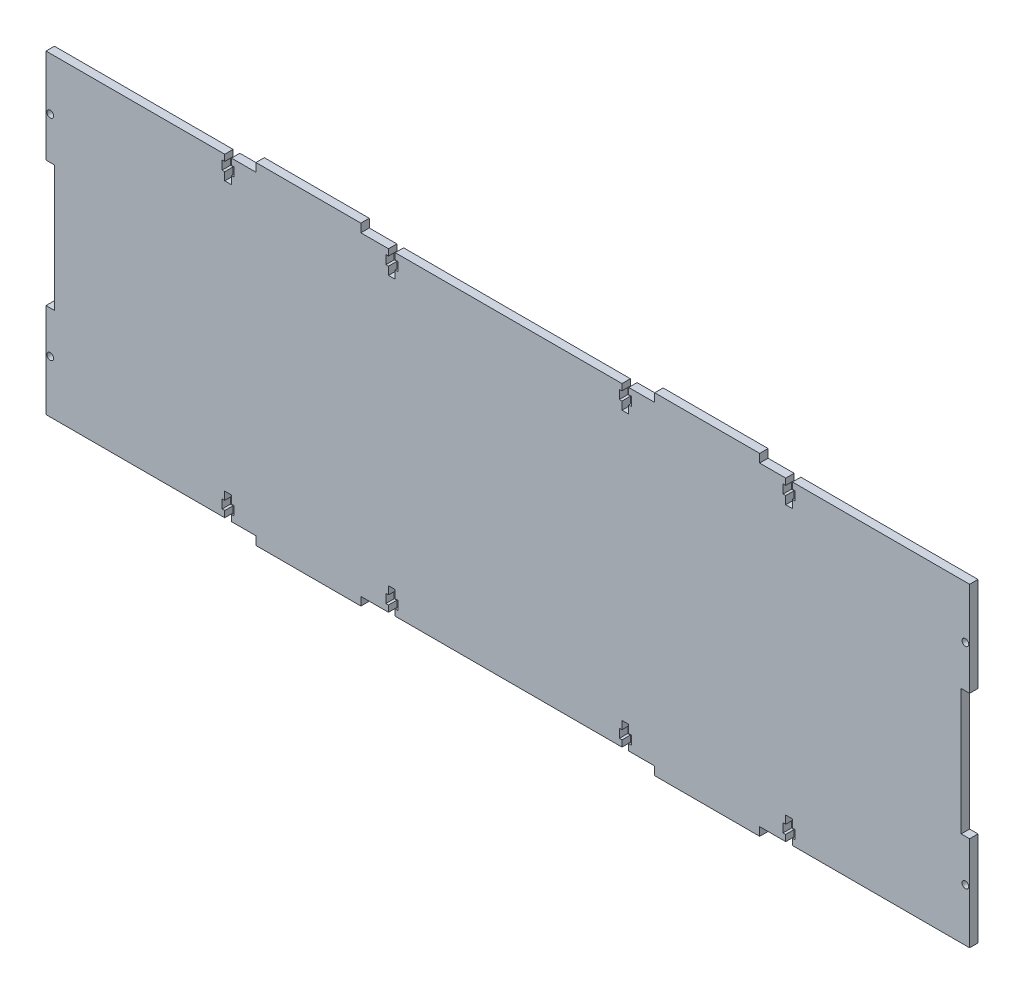
SolidWorks part; units mm, degrees
ref_plane "Plan de face" through (0, 0, 0) normal (0, 0, 1) x (1, 0, 0)
ref_plane "Plan de dessus" through (0, 0, 0) normal (0, 1, 0) x (1, 0, 0)
ref_plane "Plan de droite" through (0, 0, 0) normal (1, 0, 0) x (0, 0, -1)
sketch "Esquisse1" plane through (0, 0, 0) normal (0, 0, 1) x (1, 0, 0)
  line L1 (220, -75) -> (-220, -75)
  line L2 (220, -75) -> (220, 75)
  line L3 (220, 75) -> (-220, 75)
  line L4 (-220, -75) -> (-220, 75)
  line L5 (220, -75) -> (-220, 75) construction
  line L6 (220, 75) -> (-220, -75) construction
  point P0 (0, 0)
  dimension "D1" = 440
  dimension "D2" = 150
extrude "Boss.-Extru.1" add sketch "Esquisse1" along normal blind 4
sketch "Esquisse2" plane through (0, 0, 4) normal (0, 0, 1) x (1, 0, 0)
  line L0 (-220, 75) -> (-220, -75) construction
  line L1 (-216, 30) -> (-220, 30)
  line L2 (-216, 30) -> (-216, -30)
  line L3 (-216, -30) -> (-220, -30)
  line L4 (-220, 30) -> (-220, -30)
  line L5 (-216, -30) -> (-220, -30) construction
  line L6 (220, 30) -> (216, 30) construction
  line L7 (216, 30) -> (220, 30)
  line L8 (216, 30) -> (216, -30)
  line L9 (216, -30) -> (220, -30)
  line L10 (220, 30) -> (220, -30)
  line L11 (220, -30) -> (216, -30) construction
  line L12 (220, -75) -> (220, 75) construction
  line L13 (216, -30) -> (216, 30) construction
  dimension "D1" = 0
extrude "Enlèv. mat.-Extru.1" cut sketch "Esquisse2" against normal blind 4
sketch "Esquisse3" plane through (0, 0, 4) normal (0, 0, 1) x (1, 0, 0)
  line L0 (-70, -75) -> (-70, -79) construction
  line L1 (-120, -79) -> (-70, -79)
  line L2 (-120, -79) -> (-120, -75)
  line L3 (-120, -75) -> (-70, -75)
  line L4 (-70, -79) -> (-70, -75)
  line L5 (-220, -75) -> (220, -75) construction
  line L6 (120, -75) -> (120, -79) construction
  line L7 (70, -79) -> (120, -79)
  line L8 (70, -79) -> (70, -75)
  line L9 (70, -75) -> (120, -75)
  line L10 (120, -79) -> (120, -75)
  line L11 (-90.2276, 0) -> (85.2541, 0) construction
  line L12 (70, 79) -> (70, 75)
  line L13 (70, 79) -> (120, 79)
  line L14 (70, 75) -> (120, 75)
  line L15 (120, 79) -> (120, 75)
  line L16 (-70, 79) -> (-70, 75)
  line L17 (-120, 79) -> (-70, 79)
  line L18 (-120, 75) -> (-70, 75)
  line L19 (-120, 79) -> (-120, 75)
extrude "Boss.-Extru.2" add sketch "Esquisse3" against normal blind 4
sketch "Esquisse4" plane through (0, 0, 4) normal (0, 0, 1) x (1, 0, 0)
  line L0 (220, 75) -> (120, 75) construction
  line L1 (132.4, 75) -> (135.6, 75)
  line L2 (132.4, 75) -> (132.4, 72)
  line L3 (132.4, 64) -> (135.6, 64)
  line L5 (132.4, 79) -> (132.4, 75) construction
  line L6 (220.3751, 79) -> (120, 79) construction
  line L7 (132.4, 67.8) -> (131.15, 67.8)
  line L8 (136.85, 67.8) -> (135.6, 67.8)
  line L9 (136.85, 67.8) -> (136.85, 72)
  line L10 (136.85, 72) -> (135.6, 72)
  line L11 (131.15, 67.8) -> (131.15, 72)
  line L12 (136.85, 67.8) -> (131.15, 72) construction
  line L13 (136.85, 72) -> (131.15, 67.8) construction
  line L14 (132.4, 72) -> (131.15, 72)
  line L15 (132.4, 67.8) -> (132.4, 64)
  line L16 (135.6, 67.8) -> (135.6, 64)
  line L17 (135.6, 75) -> (135.6, 72)
  line L18 (54.4, 75) -> (57.6, 75)
  line L19 (54.4, 75) -> (54.4, 72)
  line L20 (54.4, 64) -> (57.6, 64)
  line L21 (54.4, 67.8) -> (53.15, 67.8)
  line L22 (58.85, 67.8) -> (57.6, 67.8)
  line L23 (58.85, 67.8) -> (58.85, 72)
  line L24 (58.85, 72) -> (57.6, 72)
  line L25 (53.15, 67.8) -> (53.15, 72)
  line L26 (58.85, 67.8) -> (53.15, 72) construction
  line L27 (58.85, 72) -> (53.15, 67.8) construction
  line L28 (54.4, 72) -> (53.15, 72)
  line L29 (54.4, 67.8) -> (54.4, 64)
  line L30 (57.6, 67.8) -> (57.6, 64)
  line L31 (57.6, 75) -> (57.6, 72)
  line L32 (54.4, 79) -> (54.4, 75) construction
  line L33 (70, 75) -> (-70, 75) construction
  line L34 (-56.8497, 75) -> (-53.6497, 75)
  line L35 (-56.8497, 75) -> (-56.8497, 72)
  line L36 (-56.8497, 64) -> (-53.6497, 64)
  line L37 (-56.8497, 67.8) -> (-58.0997, 67.8)
  line L38 (-52.3997, 67.8) -> (-53.6497, 67.8)
  line L39 (-52.3997, 67.8) -> (-52.3997, 72)
  line L40 (-52.3997, 72) -> (-53.6497, 72)
  line L41 (-58.0997, 67.8) -> (-58.0997, 72)
  line L42 (-52.3997, 67.8) -> (-58.0997, 72) construction
  line L43 (-52.3997, 72) -> (-58.0997, 67.8) construction
  line L44 (-56.8497, 72) -> (-58.0997, 72)
  line L45 (-56.8497, 67.8) -> (-56.8497, 64)
  line L46 (-53.6497, 67.8) -> (-53.6497, 64)
  line L47 (-53.6497, 75) -> (-53.6497, 72)
  line L48 (-134.8497, 75) -> (-131.6497, 75)
  line L49 (-56.8497, 79) -> (-56.8497, 75) construction
  line L50 (-134.8497, 75) -> (-134.8497, 72)
  line L51 (-134.8497, 64) -> (-131.6497, 64)
  line L52 (-134.8497, 67.8) -> (-136.0997, 67.8)
  line L53 (-130.3997, 67.8) -> (-131.6497, 67.8)
  line L54 (-130.3997, 67.8) -> (-130.3997, 72)
  line L55 (-130.3997, 72) -> (-131.6497, 72)
  line L56 (-136.0997, 67.8) -> (-136.0997, 72)
  line L57 (-130.3997, 67.8) -> (-136.0997, 72) construction
  line L58 (-130.3997, 72) -> (-136.0997, 67.8) construction
  line L59 (-134.8497, 72) -> (-136.0997, 72)
  line L60 (-134.8497, 67.8) -> (-134.8497, 64)
  line L61 (-131.6497, 67.8) -> (-131.6497, 64)
  line L62 (-131.6497, 75) -> (-131.6497, 72)
  line L63 (-134.8497, 79) -> (-134.8497, 75) construction
  line L64 (-120, 75) -> (-220, 75) construction
  line L65 (160.5028, 0) -> (-158.391, 0) construction
  line L66 (-130.3997, -72) -> (-136.0997, -67.8) construction
  line L67 (-130.3997, -67.8) -> (-136.0997, -72) construction
  line L68 (-52.3997, -72) -> (-58.0997, -67.8) construction
  line L69 (-52.3997, -67.8) -> (-58.0997, -72) construction
  line L70 (58.85, -72) -> (53.15, -67.8) construction
  line L71 (58.85, -67.8) -> (53.15, -72) construction
  line L72 (136.85, -72) -> (131.15, -67.8) construction
  line L73 (136.85, -67.8) -> (131.15, -72) construction
  line L74 (-131.6497, -75) -> (-131.6497, -72)
  line L75 (-131.6497, -67.8) -> (-131.6497, -64)
  line L76 (-134.8497, -67.8) -> (-134.8497, -64)
  line L77 (-134.8497, -72) -> (-136.0997, -72)
  line L78 (-136.0997, -67.8) -> (-136.0997, -72)
  line L79 (-130.3997, -72) -> (-131.6497, -72)
  line L80 (-130.3997, -67.8) -> (-130.3997, -72)
  line L81 (-130.3997, -67.8) -> (-131.6497, -67.8)
  line L82 (-134.8497, -67.8) -> (-136.0997, -67.8)
  line L83 (-134.8497, -64) -> (-131.6497, -64)
  line L84 (-134.8497, -75) -> (-134.8497, -72)
  line L85 (-134.8497, -75) -> (-131.6497, -75)
  line L86 (-53.6497, -75) -> (-53.6497, -72)
  line L87 (-53.6497, -67.8) -> (-53.6497, -64)
  line L88 (-56.8497, -67.8) -> (-56.8497, -64)
  line L89 (-56.8497, -72) -> (-58.0997, -72)
  line L90 (-58.0997, -67.8) -> (-58.0997, -72)
  line L91 (-52.3997, -72) -> (-53.6497, -72)
  line L92 (-52.3997, -67.8) -> (-52.3997, -72)
  line L93 (-52.3997, -67.8) -> (-53.6497, -67.8)
  line L94 (-56.8497, -67.8) -> (-58.0997, -67.8)
  line L95 (-56.8497, -64) -> (-53.6497, -64)
  line L96 (-56.8497, -75) -> (-56.8497, -72)
  line L97 (-56.8497, -75) -> (-53.6497, -75)
  line L98 (57.6, -75) -> (57.6, -72)
  line L99 (57.6, -67.8) -> (57.6, -64)
  line L100 (54.4, -67.8) -> (54.4, -64)
  line L101 (54.4, -72) -> (53.15, -72)
  line L102 (53.15, -67.8) -> (53.15, -72)
  line L103 (58.85, -72) -> (57.6, -72)
  line L104 (58.85, -67.8) -> (58.85, -72)
  line L105 (58.85, -67.8) -> (57.6, -67.8)
  line L106 (54.4, -67.8) -> (53.15, -67.8)
  line L107 (54.4, -64) -> (57.6, -64)
  line L108 (54.4, -75) -> (54.4, -72)
  line L109 (54.4, -75) -> (57.6, -75)
  line L110 (135.6, -75) -> (135.6, -72)
  line L111 (135.6, -67.8) -> (135.6, -64)
  line L112 (132.4, -67.8) -> (132.4, -64)
  line L113 (132.4, -72) -> (131.15, -72)
  line L114 (131.15, -67.8) -> (131.15, -72)
  line L115 (136.85, -72) -> (135.6, -72)
  line L116 (136.85, -67.8) -> (136.85, -72)
  line L117 (136.85, -67.8) -> (135.6, -67.8)
  line L118 (132.4, -67.8) -> (131.15, -67.8)
  line L119 (132.4, -64) -> (135.6, -64)
  line L120 (132.4, -75) -> (132.4, -72)
  line L121 (132.4, -75) -> (135.6, -75)
  point P10 (134, 69.9)
  point P23 (56, 69.9)
  point P40 (-55.2497, 69.9)
  point P55 (-133.2497, 69.9)
  point P119 (-133.2497, -69.9)
  point P120 (-55.2497, -69.9)
  point P121 (56, -69.9)
  point P122 (134, -69.9)
  dimension "D1" = 3.2
  dimension "D2" = 15
  dimension "D3" = 5.7
  dimension "D4" = 4.2
  dimension "D5" = 3
  dimension "D6" = 1.25
  dimension "D7" = 1.25
  dimension "D8" = 1.25
  dimension "D9" = 3.8
  dimension "D10" = 3.2
  dimension "D11" = 5.7
  dimension "D12" = 4.2
  dimension "D13" = 3
  dimension "D14" = 1.25
  dimension "D15" = 1.25
  dimension "D16" = 1.25
  dimension "D17" = 3.8
  dimension "D18" = 0
  dimension "D19" = 11
  dimension "D20" = 3.2
  dimension "D21" = 5.7
  dimension "D22" = 4.2
  dimension "D23" = 3
  dimension "D24" = 1.25
  dimension "D25" = 1.25
  dimension "D26" = 1.25
  dimension "D27" = 3.8
  dimension "D28" = 11
  dimension "D29" = 0
  dimension "D30" = 0
  dimension "D31" = 3.2
  dimension "D32" = 5.7
  dimension "D33" = 4.2
  dimension "D34" = 3
  dimension "D35" = 1.25
  dimension "D36" = 1.25
  dimension "D37" = 1.25
  dimension "D38" = 3.8
  dimension "D39" = 11
  dimension "D40" = 0
  dimension "D41" = 0
extrude "Enlèv. mat.-Extru.2" cut sketch "Esquisse4" against normal blind 10
sketch "Esquisse5" plane through (0, 0, 4) normal (0, 0, 1) x (1, 0, 0)
  line L0 (0, 29.2626) -> (0, -36.2467) construction
  circle A0 centre (218, -50) radius 1.6 construction
  circle A1 centre (218, 50) radius 1.6 construction
  circle A2 centre (218, -50) radius 1.6
  circle A3 centre (218, 50) radius 1.6
  circle A4 centre (-218, 50) radius 1.6
  circle A5 centre (-218, -50) radius 1.6
extrude "Enlèv. mat.-Extru.3" cut sketch "Esquisse5" against normal blind 4
